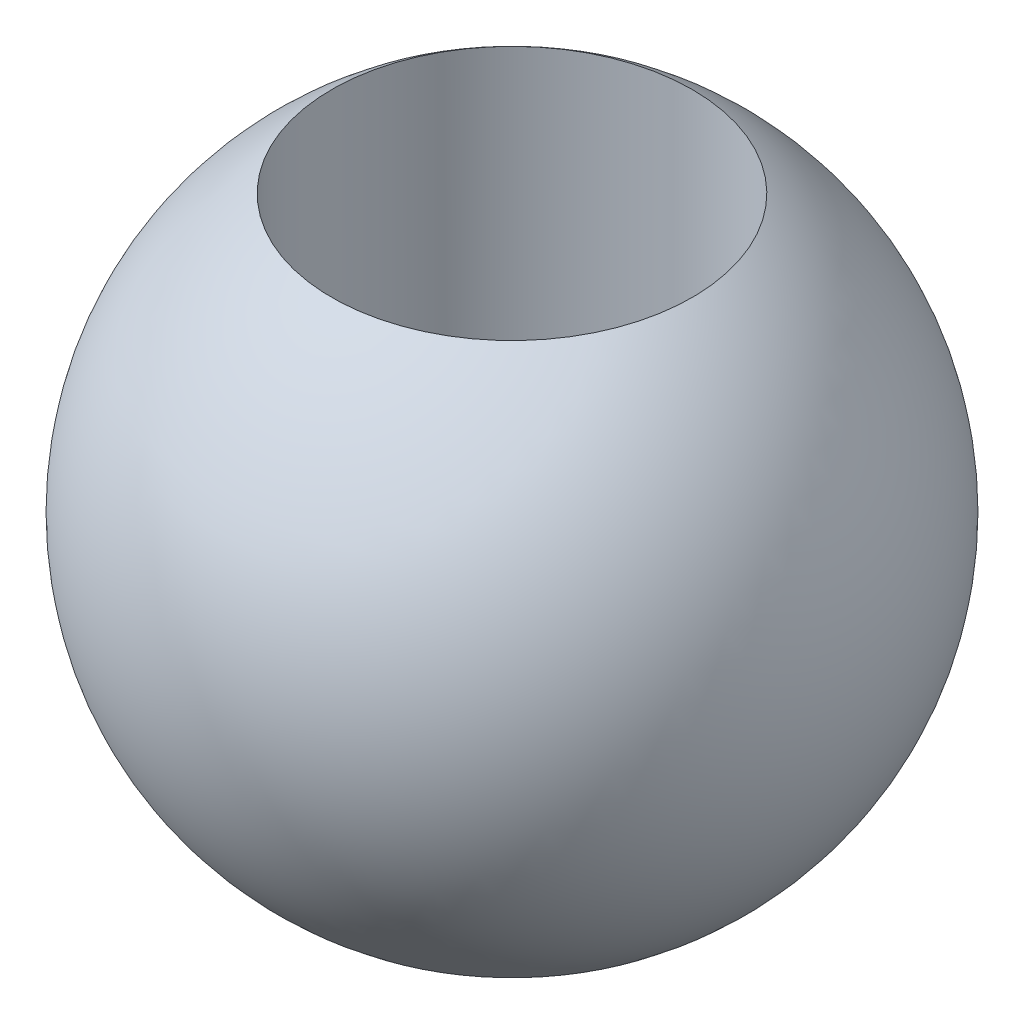
SolidWorks part; units mm, degrees
ref_plane "Front" through (0, 0, 0) normal (0, 0, 1) x (1, 0, 0)
ref_plane "Top" through (0, 0, 0) normal (0, 1, 0) x (1, 0, 0)
ref_plane "Right" through (0, 0, 0) normal (1, 0, 0) x (0, 0, -1)
sketch "Sketch1" plane through (0, 0, 0) normal (0, 0, 1) x (1, 0, 0)
  line L0 (-3.2, 0) -> (3.2, 0)
  arc A0 (-3.2, 0) -> (3.2, 0) centre (0, 0) cw
  dimension "D1" = 3.2
revolve "Revolve1" add sketch "Sketch1" angle 360 about L0
sketch "Sketch2" plane through (0, 0, 0) normal (0, 1, 0) x (1, 0, 0)
  circle A0 centre (0, 0) radius 1.75
  dimension "D1" = 3.5
extrude "Cut-Extrude1" cut sketch "Sketch2" against normal through all both and the other way through all
